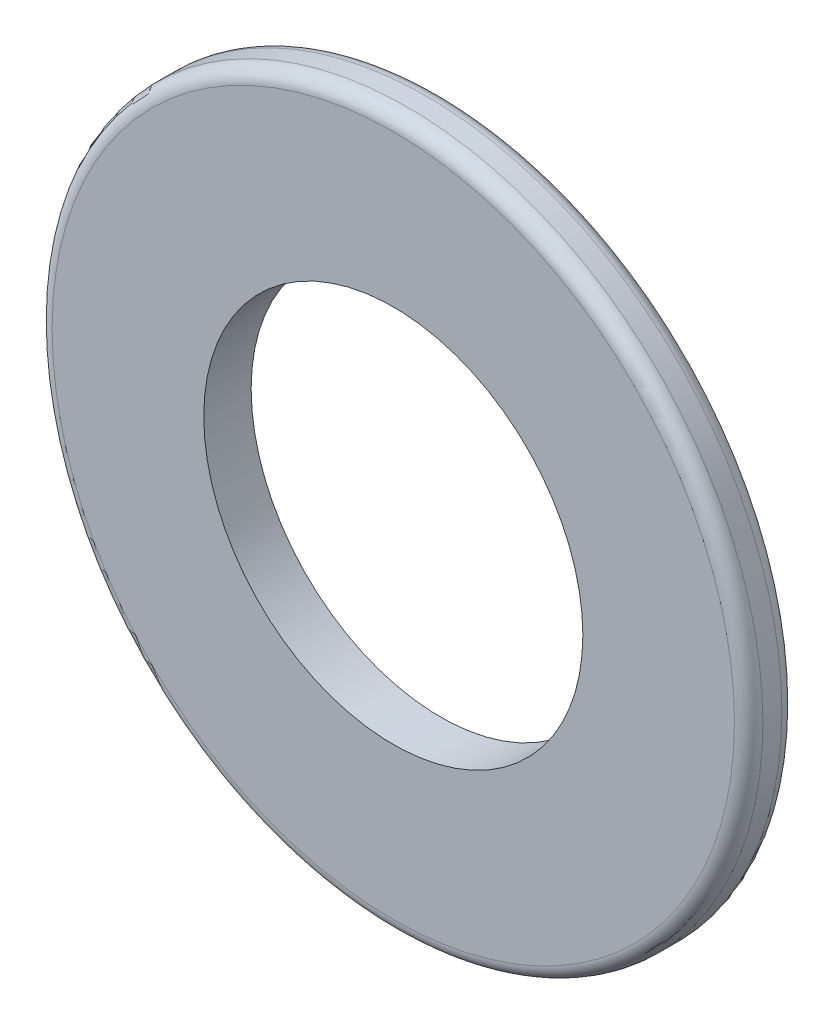
SolidWorks part; units mm, degrees
ref_plane "Front Plane" through (0, 0, 0) normal (0, 0, 1) x (1, 0, 0)
ref_plane "Top Plane" through (0, 0, 0) normal (0, 1, 0) x (1, 0, 0)
ref_plane "Right Plane" through (0, 0, 0) normal (1, 0, 0) x (0, 0, -1)
sketch "Sketch2" plane through (0, 0, 0) normal (0, 0, 1) x (1, 0, 0)
  circle A0 centre (0, 0) radius 7.5
  circle A1 centre (0, 0) radius 4
  dimension "D1" = 8
  dimension "D2" = 15
extrude "Boss-Extrude1" add sketch "Sketch2" along normal blind 1
fillet "Fillet1" radius 0.3 1 edges at (7.5, 0, 0)
fillet "Fillet2" radius 0.3 1 edges at (7.5, 0, 1)
